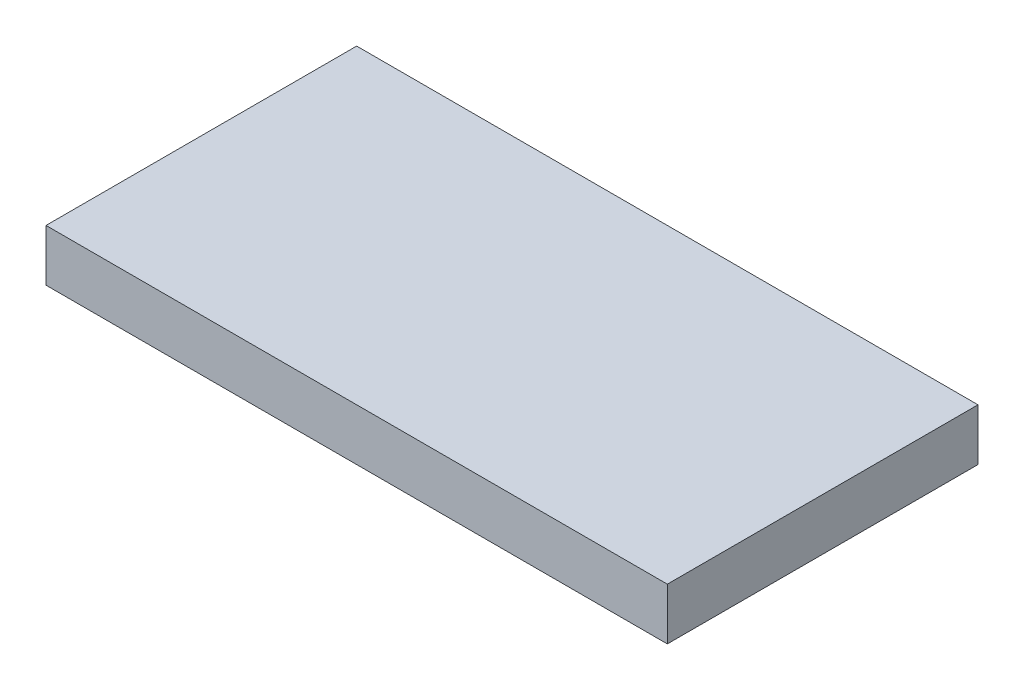
SolidWorks part; units mm, degrees
ref_plane "Front Plane" through (0, 0, 0) normal (0, 0, 1) x (1, 0, 0)
ref_plane "Top Plane" through (0, 0, 0) normal (0, 1, 0) x (1, 0, 0)
ref_plane "Right Plane" through (0, 0, 0) normal (1, 0, 0) x (0, 0, -1)
sketch "Sketch1" plane through (0, 0, 0) normal (0, 1, 0) x (1, 0, 0)
  line L1 (12, 6) -> (-12, 6)
  line L2 (12, 6) -> (12, -6)
  line L3 (12, -6) -> (-12, -6)
  line L4 (-12, 6) -> (-12, -6)
  line L5 (12, 6) -> (-12, -6) construction
  line L6 (12, -6) -> (-12, 6) construction
  point P0 (0, 0)
  dimension "D1" = 24
  dimension "D2" = 12
extrude "Boss-Extrude1" add sketch "Sketch1" along normal blind 2
